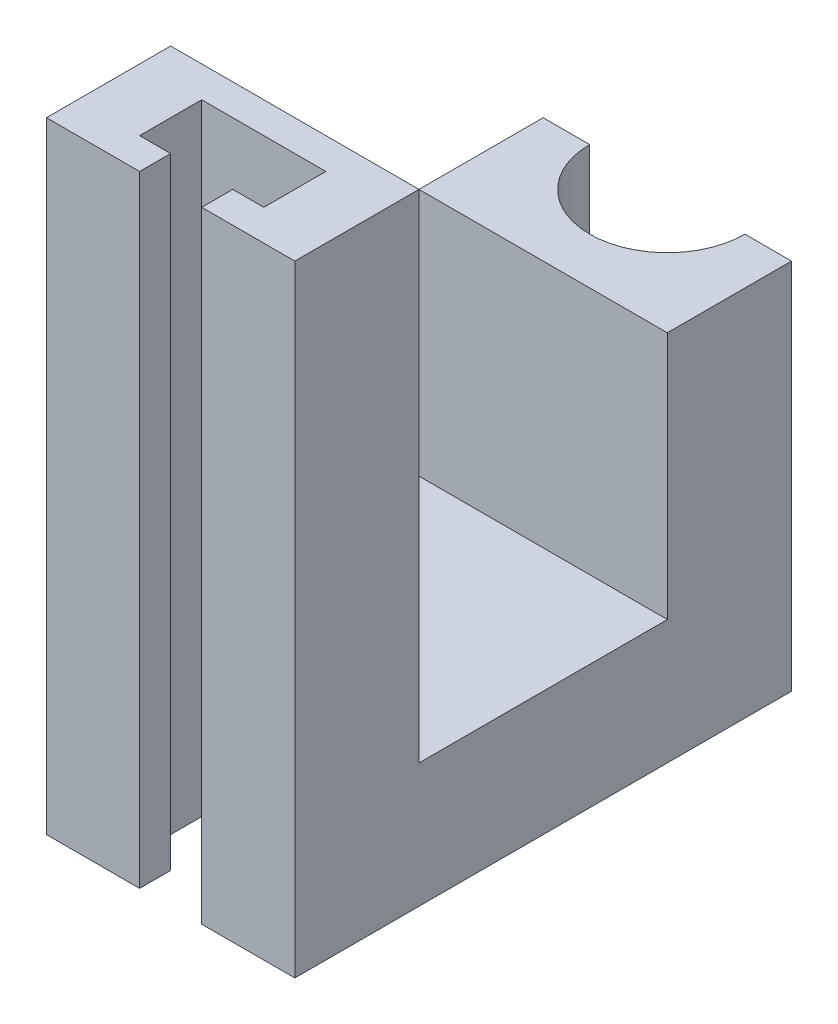
SolidWorks part; units mm, degrees
ref_plane "Front Plane" through (0, 0, 0) normal (0, 0, 1) x (1, 0, 0)
ref_plane "Top Plane" through (0, 0, 0) normal (0, 1, 0) x (1, 0, 0)
ref_plane "Right Plane" through (0, 0, 0) normal (1, 0, 0) x (0, 0, -1)
sketch "Sketch1" plane through (0, 0, 0) normal (0, 1, 0) x (1, 0, 0)
  line L0 (-3.3408, 15.7152) -> (16.6592, 15.7152)
  line L1 (-13.3408, 0.7152) -> (26.6592, 0.7152)
  line L2 (-13.3408, 0.7152) -> (-13.3408, 80.7152)
  line L3 (-13.3408, 80.7152) -> (26.6592, 80.7152)
  line L4 (26.6592, 0.7152) -> (26.6592, 80.7152)
  line L5 (16.6592, 15.7152) -> (16.6592, 5.7152)
  line L6 (16.6592, 5.7152) -> (11.6592, 5.7152)
  line L7 (11.6592, 5.7152) -> (11.6592, 0.7152)
  line L8 (11.6592, 0.7152) -> (1.6592, 0.7152)
  line L9 (1.6592, 0.7152) -> (1.6592, 5.7152)
  line L10 (1.6592, 5.7152) -> (-3.3408, 5.7152)
  line L11 (-3.3408, 5.7152) -> (-3.3408, 15.7152)
  circle A0 centre (6.6592, 80.7152) radius 12.5
  point P6 (6.6592, 15.7152)
  point P13 (6.6592, 0.7152)
  point P16 (0, 0)
  dimension "D9" = 25
  dimension "D1" = 40
  dimension "D2" = 80
  dimension "D3" = 20
  dimension "D4" = 15
  dimension "D5" = 10
  dimension "D6" = 5
  dimension "D7" = 5
  dimension "D8" = 10
extrude "Boss-Extrude1" add sketch "Sketch1" along normal blind 100 contours A0 L3 L2 L1 L9 L10 L11 L0 L5 L6 L7 L4
sketch "Sketch2" plane through (-13.3408, 0, 0) normal (-1, 0, 0) x (0, 0, 1)
  line L0 (-60.7152, 100) -> (-60.7152, 20)
  line L2 (-0.7152, 100) -> (-80.7152, 100) construction
  line L3 (-60.7152, 20) -> (-20.7152, 20)
  line L4 (-20.7152, 20) -> (-20.7152, 100)
  line L5 (-20.7152, 100) -> (-60.7152, 100)
  line L6 (-0.7152, 100) -> (-0.7152, 0) construction
  dimension "D1" = 20
  dimension "D2" = 80
  dimension "D3" = 40
extrude "Cut-Extrude1" cut sketch "Sketch2" against normal up to next contours L5 L0 L3 L4
sketch "Sketch3" plane through (-13.3408, 0, 0) normal (-1, 0, 0) x (0, 0, 1)
  line L0 (-80.7152, 0) -> (-80.7152, 60)
  line L1 (-80.7152, 100) -> (-80.7152, 0) construction
  line L2 (-80.7152, 60) -> (-60.7152, 60)
  line L3 (-60.7152, 100) -> (-60.7152, 20) construction
  line L4 (-60.7152, 60) -> (-60.7152, 0)
  line L5 (-0.7152, 0) -> (-80.7152, 0) construction
  line L6 (-60.7152, 0) -> (-80.7152, 0)
  line L7 (-80.7152, 60) -> (-80.7152, 100)
  line L8 (-80.7152, 100) -> (-60.7152, 100)
  line L9 (-60.7152, 100) -> (-60.7152, 60)
  line M7 (-60.7152, 20) -> (-60.7152, 100)
  line M8 (-60.7152, 100) -> (-80.7152, 100)
  line M9 (-80.7152, 100) -> (-80.7152, 0)
  dimension "D1" = 60
extrude "Cut-Extrude2" cut sketch "Sketch3" against normal up to next contours L2 M9 M7 M8
